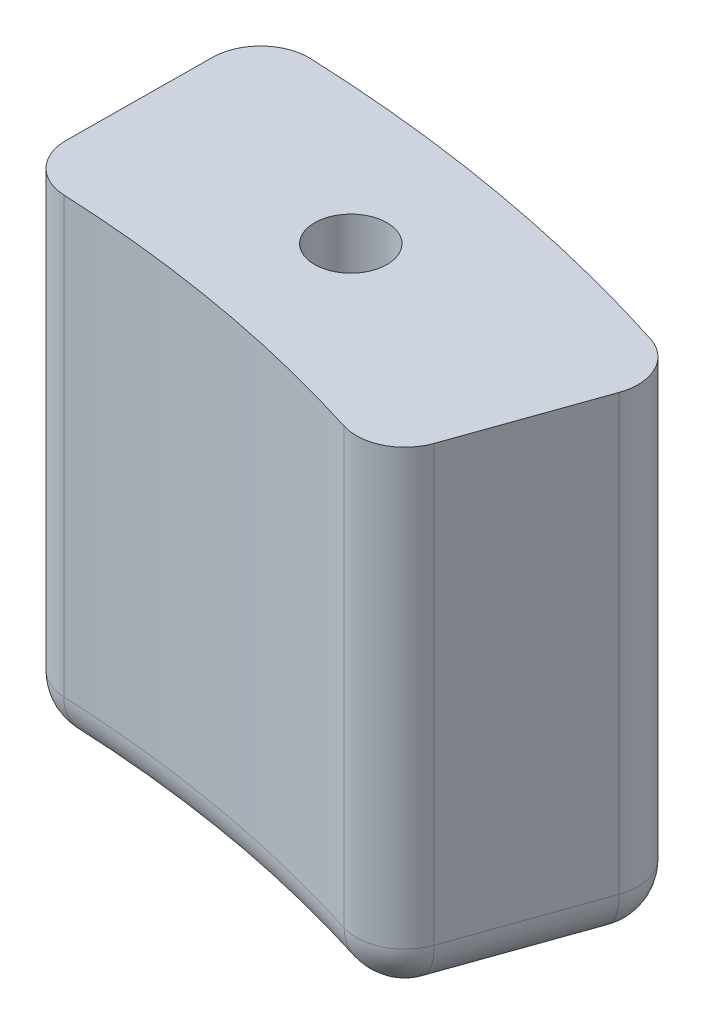
SolidWorks part; units mm, degrees
ref_plane "前视基准面" through (0, 0, 0) normal (0, 0, 1) x (1, 0, 0)
ref_plane "上视基准面" through (0, 0, 0) normal (0, 1, 0) x (1, 0, 0)
ref_plane "右视基准面" through (0, 0, 0) normal (1, 0, 0) x (0, 0, -1)
sketch "草图1" plane through (0, 0, 0) normal (0, 1, 0) x (1, 0, 0)
  line L0 (0, -5) -> (0, 5) construction
  line L1 (0.4955, 54.9978) -> (0.5856, 64.9974)
  line L2 (-0.4955, 54.9978) -> (-0.5856, 64.9974)
  line L3 (18.3447, 51.8505) -> (21.6801, 61.2778)
  line L4 (19.276, 51.5115) -> (22.7807, 60.8773)
  circle A0 centre (0, 0) radius 55
  circle A1 centre (0, 0) radius 65
  circle A2 centre (0, 55.5) radius 0.5 construction
  point P19 (0, 0)
  dimension "D1" = 110
  dimension "D2" = 10
  dimension "D3" = 1
  dimension "D5" = 18.3447
  dimension "D4" = 2
extrude "凸台-拉伸1" add sketch "草图1" along normal blind 20 contours L3 A1 L1 A0
fillet "圆角1" radius 2 8 edges at (0.5405, 0, -59.9976) (11.2871, 0, -64.0125) (20.0124, 0, -56.5641) (21.6801, 10, -61.2778) (18.3447, 10, -51.8505) (9.5506, 0, -54.1644) (0.4955, 10, -54.9978) (0.5856, 10, -64.9974)
sketch "草图2" plane through (0, 20, 0) normal (0, 1, 0) x (1, 0, 0)
  circle A0 centre (10.1115, 59.1418) radius 1.5
  circle A1 centre (0, 0) radius 60
  arc A2 (19.7239, 61.9352) -> (2.6487, 64.946) centre (0, 0) ccw construction
  point P5 (10.0726, 58.9143)
  dimension "D1" = 5
  dimension "D2" = 3
extrude "切除-拉伸1" cut sketch "草图2" against normal blind 10 contours A0 A1 | A1 A0
